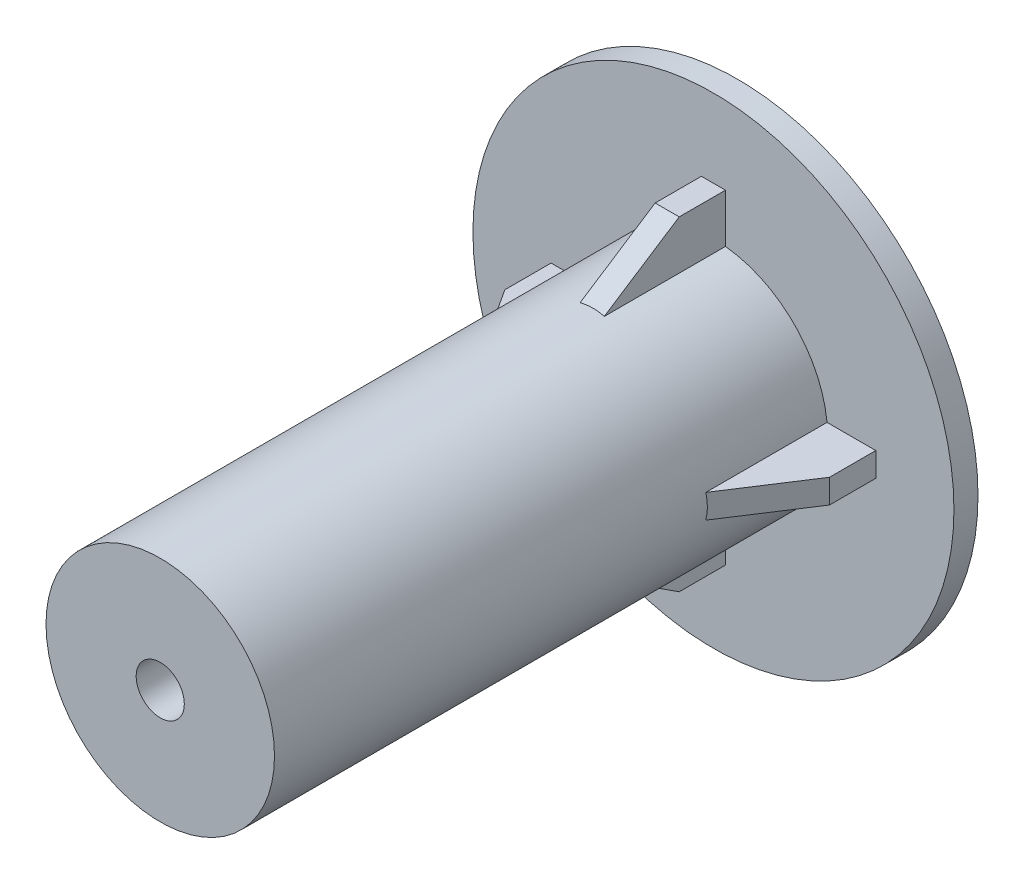
SolidWorks part; units mm, degrees
ref_plane "Front Plane" through (0, 0, 0) normal (0, 0, 1) x (1, 0, 0)
ref_plane "Top Plane" through (0, 0, 0) normal (0, 1, 0) x (1, 0, 0)
ref_plane "Right Plane" through (0, 0, 0) normal (1, 0, 0) x (0, 0, -1)
sketch "Sketch1" plane through (0, 0, 0) normal (0, 0, 1) x (1, 0, 0)
  circle A0 centre (0, 0) radius 47.5
  dimension "D1" = 95
extrude "Boss-Extrude1" add sketch "Sketch1" along normal blind 230
sketch "Sketch2" plane through (0, 0, 230) normal (0, 0, 1) x (1, 0, 0)
  circle A0 centre (0, 0) radius 10
  dimension "D1" = 20
extrude "Cut-Extrude1" cut sketch "Sketch2" against normal blind 20
sketch "Sketch3" plane through (0, 0, 0) normal (0, 0, -1) x (-1, 0, 0)
  circle A0 centre (0, 0) radius 100
  dimension "D1" = 200
extrude "Boss-Extrude2" add sketch "Sketch3" along normal blind 10
sketch "Sketch4" plane through (0, 0, 0) normal (0, 1, 0) x (1, 0, 0)
  line L0 (-47.5, -50) -> (-80, 0)
  line L1 (-47.5, 0) -> (-47.5, -230) construction
  line L2 (-100, 0) -> (100, 0) construction
  dimension "D1" = 50
  dimension "D2" = 80
rib "Rib1" sketch "Sketch4" sketch "Sketch4" thickness 10 extrusion direction parallel to sketch draft on no parameters "D1"=10
pattern_circular "CirPattern1" count 4 over 360 about axis through (0, 0, 0) along (0, 0, 1) of "Rib1"
sketch "Sketch5" plane through (0, 0, 0) normal (0, 0, 1) x (1, 0, 0)
  line L1 (-67.5, -67.5) -> (67.5, -67.5)
  line L2 (-67.5, -67.5) -> (-67.5, 67.5)
  line L3 (-67.5, 67.5) -> (67.5, 67.5)
  line L4 (67.5, -67.5) -> (67.5, 67.5)
  line L5 (-67.5, -67.5) -> (67.5, 67.5) construction
  line L6 (-67.5, 67.5) -> (67.5, -67.5) construction
  point P0 (0, 0)
  dimension "D1" = 135
extrude "Cut-Extrude2" cut sketch "Sketch5" along normal blind 74 flip side to cut
sketch "Sketch6" plane through (0, 0, 0) normal (0, 1, 0) x (1, 0, 0)
  line L0 (0, -190) -> (0, 10) construction
  line L1 (100, 10) -> (-100, 10) construction
  line L2 (0, 10) -> (200, 10) construction
  text T0 "X0\r\n" font "Century Gothic" height 20
  text T1 "Z0\r\n" font "Century Gothic" height 20
  dimension "D1" = 200
sketch "Sketch7" plane through (0, 0, -10) normal (0, 0, -1) x (-1, 0, 0)
  line L0 (0, 0) -> (0, 200) construction
  line L1 (0, 0) -> (-200, 0) construction
  text T0 "Y0\r\n" font "Century Gothic" height 20
